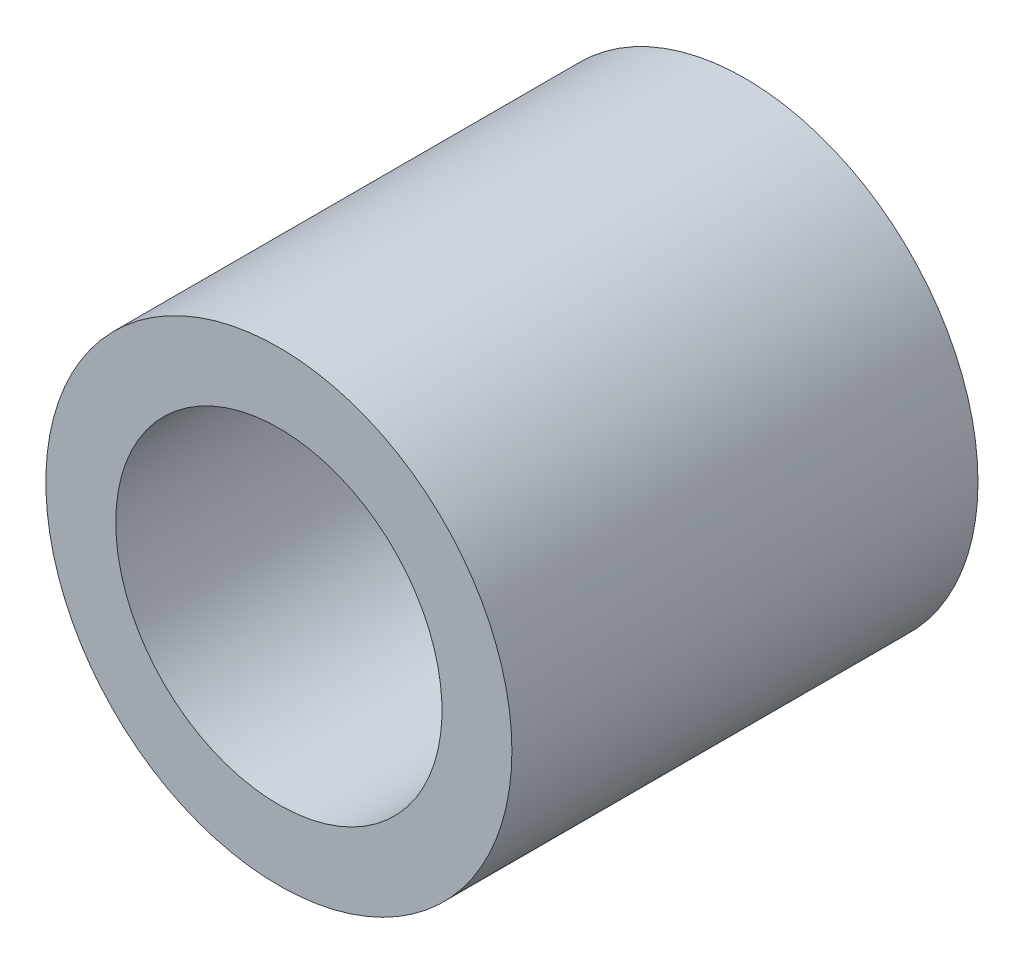
SolidWorks part; units mm, degrees
material "Plain Carbon Steel"
ref_plane "Front Plane" through (0, 0, 0) normal (0, 0, 1) x (1, 0, 0)
ref_plane "Top Plane" through (0, 0, 0) normal (0, 1, 0) x (1, 0, 0)
ref_plane "Right Plane" through (0, 0, 0) normal (1, 0, 0) x (0, 0, -1)
sketch "Sketch1" plane through (0, 0, 0) normal (0, 0, 1) x (1, 0, 0)
  circle A0 centre (0, 0) radius 20
  dimension "D1" = 40
extrude "Boss-Extrude1" add sketch "Sketch1" along normal blind 40
sketch "Sketch4" plane through (0, 0, 0) normal (0, 0, -1) x (-1, 0, 0)
  circle A0 centre (0, 0) radius 14
  dimension "D1" = 28
extrude "Cut-Extrude1" cut sketch "Sketch4" against normal blind 40
